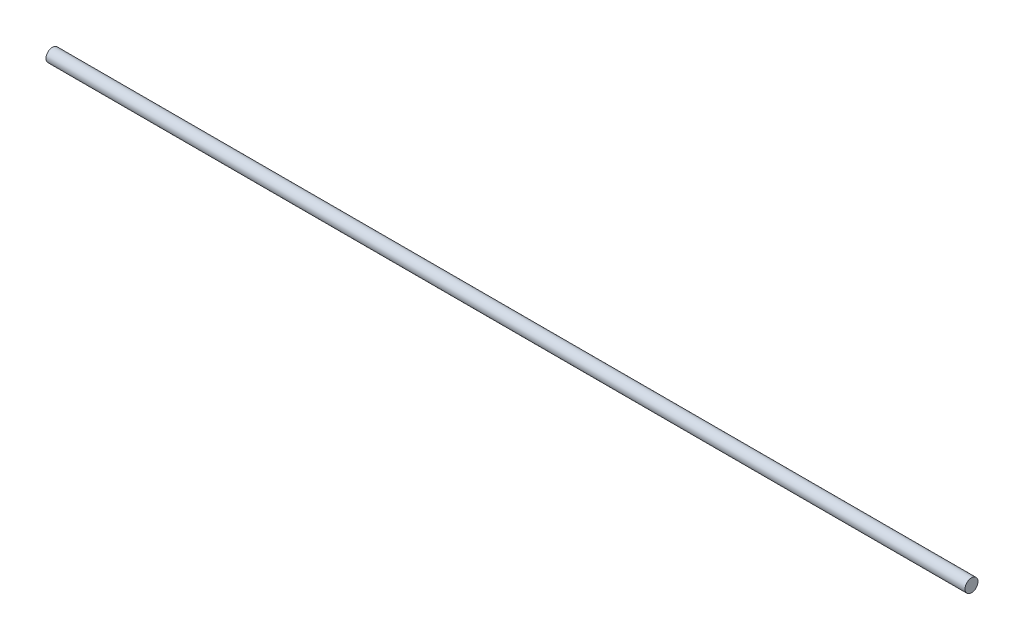
SolidWorks part; units mm, degrees
material "1060 Alloy"
ref_plane "Front Plane" through (0, 0, 0) normal (1, 0, 0) x (0, 1, 0)
ref_plane "Top Plane" through (0, 0, 0) normal (0, 0, 1) x (0, 1, 0)
ref_plane "Right Plane" through (0, 0, 0) normal (0, 1, 0) x (-1, 0, 0)
sketch "Sketch1" plane through (0, 0, 0) normal (1, 0, 0) x (0, 1, 0)
  circle A0 centre (0, 0) radius 6.35
  dimension "D1" = 12.7
extrude "Boss-Extrude1" add sketch "Sketch1" along normal blind 897.9373
equation "\"D\"= .5'Bar Diameter"
equation "\"A\"= ( 3.14 / 4 ) * \"D\" * \"D\"'Cross-Sectional Area"
equation "\"F\"= 500'Force on Bar"
equation "\"E\"= 10007603.9'Modulus of Elasticity"
equation "\"Def\"= 0.009in'Maximum Deformation"
equation "\"L\"= ( \"E\" * \"A\" * \"Def\" ) / ( \"F\" )'Bar Length (in)"
equation "\"D1@Sketch1\"=\"D\""
equation "\"D1@Boss-Extrude1\"=\"L\""
